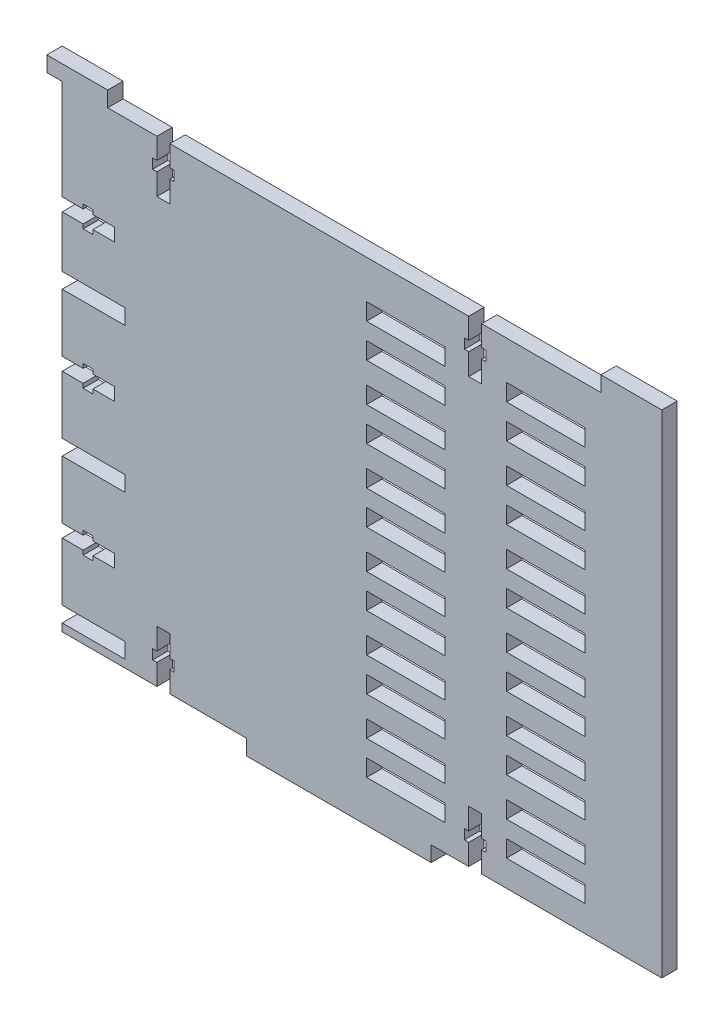
SolidWorks part; units mm, degrees
ref_plane "Front Plane" through (0, 0, 0) normal (0, 0, 1) x (1, 0, 0)
ref_plane "Top Plane" through (0, 0, 0) normal (0, 1, 0) x (1, 0, 0)
ref_plane "Right Plane" through (0, 0, 0) normal (1, 0, 0) x (0, 0, -1)
sketch "Sketch1" plane through (0, 0, 0) normal (0, 0, 1) x (1, 0, 0)
  line L0 (-45.5, 11) -> (-45.5, 16.5)
  line L1 (0, 0) -> (-25.5, 0)
  line L2 (0, 0) -> (0, 5.5)
  line L3 (0, 5.5) -> (-25.5, 5.5)
  line L4 (-25.5, 0) -> (-25.5, 5.5)
  line L5 (-45.5, 0) -> (-71, 0)
  line L6 (-45.5, 0) -> (-45.5, 5.5)
  line L7 (-45.5, 5.5) -> (-71, 5.5)
  line L8 (-71, 0) -> (-71, 5.5)
  line L9 (-45.5, 11) -> (-71, 11)
  line L10 (-71, 11) -> (-71, 16.5)
  line L11 (-45.5, 16.5) -> (-71, 16.5)
  line L12 (0, 11) -> (0, 16.5)
  line L13 (0, 11) -> (-25.5, 11)
  line L14 (-25.5, 11) -> (-25.5, 16.5)
  line L15 (0, 16.5) -> (-25.5, 16.5)
  line L16 (0, 23.5) -> (0, 29)
  line L17 (0, 23.5) -> (-25.5, 23.5)
  line L18 (-25.5, 23.5) -> (-25.5, 29)
  line L19 (0, 29) -> (-25.5, 29)
  line L20 (-45.5, 23.5) -> (-45.5, 29)
  line L21 (-45.5, 23.5) -> (-71, 23.5)
  line L22 (-71, 23.5) -> (-71, 29)
  line L23 (-45.5, 29) -> (-71, 29)
  line L24 (-45.5, 34.5) -> (-45.5, 40)
  line L25 (-45.5, 40) -> (-71, 40)
  line L26 (-71, 34.5) -> (-71, 40)
  line L27 (-45.5, 34.5) -> (-71, 34.5)
  line L28 (0, 34.5) -> (0, 40)
  line L29 (0, 40) -> (-25.5, 40)
  line L30 (-25.5, 34.5) -> (-25.5, 40)
  line L31 (0, 34.5) -> (-25.5, 34.5)
  line L32 (0, 47) -> (0, 52.5)
  line L33 (0, 47) -> (-25.5, 47)
  line L34 (-25.5, 47) -> (-25.5, 52.5)
  line L35 (0, 52.5) -> (-25.5, 52.5)
  line L36 (-45.5, 47) -> (-45.5, 52.5)
  line L37 (-45.5, 47) -> (-71, 47)
  line L38 (-71, 47) -> (-71, 52.5)
  line L39 (-45.5, 52.5) -> (-71, 52.5)
  line L40 (-45.5, 58) -> (-45.5, 63.5)
  line L41 (-45.5, 63.5) -> (-71, 63.5)
  line L42 (-71, 58) -> (-71, 63.5)
  line L43 (-45.5, 58) -> (-71, 58)
  line L44 (0, 58) -> (0, 63.5)
  line L45 (0, 63.5) -> (-25.5, 63.5)
  line L46 (-25.5, 58) -> (-25.5, 63.5)
  line L47 (0, 58) -> (-25.5, 58)
  line L48 (0, 70.5) -> (0, 76)
  line L49 (0, 70.5) -> (-25.5, 70.5)
  line L50 (-25.5, 70.5) -> (-25.5, 76)
  line L51 (0, 76) -> (-25.5, 76)
  line L52 (-45.5, 70.5) -> (-45.5, 76)
  line L53 (-45.5, 70.5) -> (-71, 70.5)
  line L54 (-71, 70.5) -> (-71, 76)
  line L55 (-45.5, 76) -> (-71, 76)
  line L56 (-45.5, 81.5) -> (-45.5, 87)
  line L57 (-45.5, 87) -> (-71, 87)
  line L58 (-71, 81.5) -> (-71, 87)
  line L59 (-45.5, 81.5) -> (-71, 81.5)
  line L60 (0, 81.5) -> (0, 87)
  line L61 (0, 87) -> (-25.5, 87)
  line L62 (-25.5, 81.5) -> (-25.5, 87)
  line L63 (0, 81.5) -> (-25.5, 81.5)
  line L64 (0, 94) -> (0, 99.5)
  line L65 (0, 94) -> (-25.5, 94)
  line L66 (-25.5, 94) -> (-25.5, 99.5)
  line L67 (0, 99.5) -> (-25.5, 99.5)
  line L68 (-45.5, 94) -> (-45.5, 99.5)
  line L69 (-45.5, 94) -> (-71, 94)
  line L70 (-71, 94) -> (-71, 99.5)
  line L71 (-45.5, 99.5) -> (-71, 99.5)
  line L72 (-45.5, 105) -> (-45.5, 110.5)
  line L73 (-45.5, 110.5) -> (-71, 110.5)
  line L74 (-71, 105) -> (-71, 110.5)
  line L75 (-45.5, 105) -> (-71, 105)
  line L76 (0, 105) -> (0, 110.5)
  line L77 (0, 110.5) -> (-25.5, 110.5)
  line L78 (-25.5, 105) -> (-25.5, 110.5)
  line L79 (0, 105) -> (-25.5, 105)
  line L80 (0, 117.5) -> (0, 123)
  line L81 (0, 117.5) -> (-25.5, 117.5)
  line L82 (-25.5, 117.5) -> (-25.5, 123)
  line L83 (0, 123) -> (-25.5, 123)
  line L84 (-45.5, 117.5) -> (-45.5, 123)
  line L85 (-45.5, 117.5) -> (-71, 117.5)
  line L86 (-71, 117.5) -> (-71, 123)
  line L87 (-45.5, 123) -> (-71, 123)
  line L88 (-45.5, 128.5) -> (-45.5, 134)
  line L89 (-45.5, 134) -> (-71, 134)
  line L90 (-71, 128.5) -> (-71, 134)
  line L91 (-45.5, 128.5) -> (-71, 128.5)
  line L92 (0, 128.5) -> (0, 134)
  line L93 (0, 134) -> (-25.5, 134)
  line L94 (-25.5, 128.5) -> (-25.5, 134)
  line L95 (0, 128.5) -> (-25.5, 128.5)
  line L96 (-155.2, 151.5) -> (-155.2, 146.5)
  line L97 (-175, 151.5) -> (-155.2, 151.5)
  line L98 (-175, 151.5) -> (-175, 146.5)
  line L100 (25, 151.5) -> (25, -8.5)
  line L101 (-155.2, 146.5) -> (5.2, 146.5)
  line L102 (5.2, 146.5) -> (5.2, 151.5)
  line L103 (-141.9786, 71.5) -> (25, 71.5) construction
  line L107 (5.2, 151.5) -> (25, 151.5)
  line L109 (-175, 146.5) -> (-170, 146.5)
  line L110 (-170, 146.5) -> (-170, 114)
  line L116 (-170, 109.8) -> (-170, 93)
  line L117 (-150, 88) -> (-170, 88)
  line L118 (-170, 93) -> (-150, 93)
  line L119 (-150, 93) -> (-150, 88)
  line L123 (-150, 41) -> (-170, 41)
  line L124 (-170, 46) -> (-150, 46)
  line L125 (-150, 46) -> (-150, 41)
  line L129 (-150, -6) -> (-170, -6)
  line L130 (-170, -1) -> (-150, -1)
  line L131 (-150, -1) -> (-150, -6)
  line L132 (-170, 88) -> (-170, 69.1)
  line L133 (-170, 64.9) -> (-170, 46)
  line L134 (-170, 41) -> (-170, 22.1)
  line L135 (-170, 17.9) -> (-170, -1)
  line L137 (-170, -8.5) -> (25, -8.5)
  line L141 (-170, -6) -> (-170, -8.5)
  line L142 (-170, 114) -> (-163.2, 114)
  line L143 (-153, 114) -> (-153, 109.8)
  line L144 (-153, 109.8) -> (-160, 109.8)
  line L145 (-163.2, 114) -> (-163.2, 115.4)
  line L146 (-160, 108.4) -> (-163.2, 108.4)
  line L147 (-160, 108.4) -> (-160, 109.8)
  line L148 (-160, 115.4) -> (-163.2, 115.4)
  line L149 (-163.2, 108.4) -> (-163.2, 109.8)
  line L150 (-150.0379, 67) -> (-180.7689, 67) construction
  line L151 (-163.2, 109.8) -> (-170, 109.8)
  line L152 (-150.0379, 20) -> (-177.5047, 20) construction
  line L153 (-160, 69.1) -> (-153, 69.1)
  line L154 (-160, 114) -> (-160, 115.4)
  line L155 (-160, 114) -> (-153, 114)
  line L156 (-153, 69.1) -> (-153, 64.9)
  line L157 (-153, 64.9) -> (-160, 64.9)
  line L158 (-160, 69.1) -> (-160, 70.5)
  line L159 (-160, 70.5) -> (-163.2, 70.5)
  line L160 (-163.2, 69.1) -> (-163.2, 70.5)
  line L161 (-163.2, 63.5) -> (-163.2, 64.9)
  line L162 (-160, 63.5) -> (-163.2, 63.5)
  line L163 (-160, 63.5) -> (-160, 64.9)
  line L164 (-163.2, 64.9) -> (-170, 64.9)
  line L165 (-170, 69.1) -> (-163.2, 69.1)
  line L168 (-163.2, 17.9) -> (-170, 17.9)
  line L169 (-170, 22.1) -> (-163.2, 22.1)
  line L170 (-163.2, 22.1) -> (-163.2, 23.5)
  line L171 (-160, 23.5) -> (-163.2, 23.5)
  line L172 (-160, 22.1) -> (-160, 23.5)
  line L173 (-160, 22.1) -> (-153, 22.1)
  line L174 (-153, 22.1) -> (-153, 17.9)
  line L175 (-153, 17.9) -> (-160, 17.9)
  line L176 (-163.2, 16.5) -> (-163.2, 17.9)
  line L177 (-160, 16.5) -> (-160, 17.9)
  line L178 (-160, 16.5) -> (-163.2, 16.5)
  point P125 (-153, 20)
  point P127 (-150, 90.5)
  point P128 (-153, 67)
  point P175 (-153, 111.9)
  dimension "D1" = 25.5
  dimension "D2" = 25.5
  dimension "D3" = 20
  dimension "D4" = 5.5
  dimension "D5" = 5.5
  dimension "D7" = 11
  dimension "D9" = 200
  dimension "D10" = 25
  dimension "D11" = 4.2
  dimension "D12" = 23
  dimension "D13" = 128.5
  dimension "D14" = 5
  dimension "D15" = 19.8
  dimension "D16" = 19.8
  dimension "D17" = 5
  dimension "D18" = 155
  dimension "D19" = 18.9
  dimension "D20" = 7
  dimension "D21" = 17
  dimension "D22" = 6.8
  dimension "D23" = 3.2
  dimension "D24" = 99
  dimension "D25" = 20
  dimension "D27" = 20
  dimension "D28" = 20
  dimension "D29" = 170
  dimension "D30" = 21
  dimension "D31" = 21
  dimension "D34" = 41
  dimension "D35" = 41
  dimension "D36" = 46
  dimension "D37" = 46
  dimension "D39" = 2
  dimension "D42" = 88
  dimension "D43" = 88
  dimension "D44" = 1
  dimension "D45" = 1
  dimension "D47" = 2
  dimension "D6" = 2
  dimension "D8" = 6
extrude "Boss-Extrude1" add sketch "Sketch1" along normal blind 5
sketch "Sketch4" plane through (0, 0, 5) normal (0, 0, 1) x (1, 0, 0)
  line L0 (5.2, 146.5) -> (-155.2, 146.5) construction
  line L1 (-170, 146.5) -> (-170, 114) construction
  line L2 (-33.6, 146.5) -> (-33.6, 139.7)
  line L3 (-33.6, 139.7) -> (-32.2, 139.7)
  line L4 (-32.2, 139.7) -> (-32.2, 136.5)
  line L5 (-32.2, 136.5) -> (-33.6, 136.5)
  line L6 (-33.6, 136.5) -> (-33.6, 129.5)
  line L7 (-33.6, 129.5) -> (-37.8, 129.5)
  line L8 (-37.8, 129.5) -> (-37.8, 136.5)
  line L9 (-37.8, 136.5) -> (-39.2, 136.5)
  line L10 (-39.2, 139.7) -> (-37.8, 139.7)
  line L11 (-135, 129.5) -> (-139.2, 129.5)
  line L12 (-139.2, 129.5) -> (-139.2, 136.5)
  line L13 (-139.2, 136.5) -> (-140.6, 136.5)
  line L14 (-140.6, 136.5) -> (-140.6, 139.7)
  line L15 (-140.6, 139.7) -> (-139.2, 139.7)
  line L16 (-139.2, 139.7) -> (-139.2, 146.5)
  line L17 (-135, 146.5) -> (-135, 139.7)
  line L18 (-135, 139.7) -> (-133.6, 139.7)
  line L19 (-133.6, 139.7) -> (-133.6, 136.5)
  line L20 (-133.6, 136.5) -> (-135, 136.5)
  line L21 (-135, 136.5) -> (-135, 129.5)
  line L22 (-135, 146.5) -> (-139.2, 146.5)
  line L23 (25, -8.5) -> (25, 151.5) construction
  line L24 (-170, -8.5) -> (25, -8.5) construction
  line L25 (-39.2, 136.5) -> (-39.2, 139.7)
  line L26 (-37.8, 139.7) -> (-37.8, 146.5)
  line L27 (-33.6, 146.5) -> (-37.8, 146.5)
  line L28 (-170, 69) -> (25, 69) construction
  line L29 (-170, 88) -> (-170, 69.1) construction
  line L30 (-33.6, -8.5) -> (-37.8, -8.5)
  line L31 (-37.8, -1.7) -> (-37.8, -8.5)
  line L32 (-39.2, 1.5) -> (-39.2, -1.7)
  line L33 (-135, -8.5) -> (-139.2, -8.5)
  line L34 (-135, 1.5) -> (-135, 8.5)
  line L35 (-133.6, 1.5) -> (-135, 1.5)
  line L36 (-133.6, -1.7) -> (-133.6, 1.5)
  line L37 (-135, -1.7) -> (-133.6, -1.7)
  line L38 (-135, -8.5) -> (-135, -1.7)
  line L39 (-139.2, -1.7) -> (-139.2, -8.5)
  line L40 (-140.6, -1.7) -> (-139.2, -1.7)
  line L41 (-140.6, 1.5) -> (-140.6, -1.7)
  line L42 (-139.2, 1.5) -> (-140.6, 1.5)
  line L43 (-139.2, 8.5) -> (-139.2, 1.5)
  line L44 (-135, 8.5) -> (-139.2, 8.5)
  line L45 (-39.2, -1.7) -> (-37.8, -1.7)
  line L46 (-37.8, 1.5) -> (-39.2, 1.5)
  line L47 (-37.8, 8.5) -> (-37.8, 1.5)
  line L48 (-33.6, 8.5) -> (-37.8, 8.5)
  line L49 (-33.6, 1.5) -> (-33.6, 8.5)
  line L50 (-32.2, 1.5) -> (-33.6, 1.5)
  line L51 (-32.2, -1.7) -> (-32.2, 1.5)
  line L52 (-33.6, -1.7) -> (-32.2, -1.7)
  line L53 (-33.6, -8.5) -> (-33.6, -1.7)
  point P25 (-35.7, 138)
  point P61 (-35.7, 0)
  dimension "D1" = 160
  dimension "D2" = 160
  dimension "D3" = 4.2
  dimension "D4" = 7
  dimension "D5" = 1.4
  dimension "D6" = 30.8
  dimension "D7" = 2
extrude "Cut-Extrude3" cut sketch "Sketch4" against normal blind 10
sketch "Sketch5" plane through (0, 0, 5) normal (0, 0, 1) x (1, 0, 0)
  line L0 (-135, -8.5) -> (-37.8, -8.5) construction
  line L1 (-110, -8.5) -> (-50, -8.5)
  line L2 (-110, -8.5) -> (-110, -13.5)
  line L3 (-110, -13.5) -> (-50, -13.5)
  line L4 (-50, -8.5) -> (-50, -13.5)
  line L5 (25, -8.5) -> (25, 151.5) construction
  line L6 (-170, -6) -> (-170, -8.5) construction
  dimension "D1" = 5
  dimension "D2" = 75
  dimension "D3" = 60
extrude "Boss-Extrude2" add sketch "Sketch5" against normal blind 5
sketch "Sketch6" plane through (0, 0, 5) normal (0, 0, 1) x (1, 0, 0)
  line L0 (-170, 88) -> (-170, 69.1) construction
  line L1 (-149.6, 93) -> (-170, 93)
  line L2 (-149.6, 93) -> (-149.6, 88)
  line L3 (-149.6, 88) -> (-170, 88)
  line L4 (-170, 93) -> (-170, 88)
  line L6 (-170, 93) -> (-150, 93) construction
  line L7 (-149.6, 88) -> (-150, 46) construction
  line L8 (-150, 46) -> (-149.8, 67)
  line L9 (-149.8, 67) -> (-132.3454, 67) construction
  line L10 (-170, 41) -> (-170, 46)
  line L11 (-149.6, 46) -> (-170, 46)
  line L12 (-149.6, 41) -> (-149.6, 46)
  line L13 (-149.6, 41) -> (-170, 41)
  line L14 (-153, 20) -> (-135.0509, 20) construction
  line L15 (-153, 22.1) -> (-153, 17.9) construction
  line L16 (-149.6, -1) -> (-170, -1)
  line L17 (-149.6, -1) -> (-149.6, -6)
  line L18 (-149.6, -6) -> (-170, -6)
  line L19 (-170, -1) -> (-170, -6)
  dimension "D1" = 20.4
  dimension "D2" = 5
extrude "Cut-Extrude4" cut sketch "Sketch6" against normal blind 10 contours L16 L19 L18 L17 | L13 L12 L11 L10 | L1 L4 L3 L2
